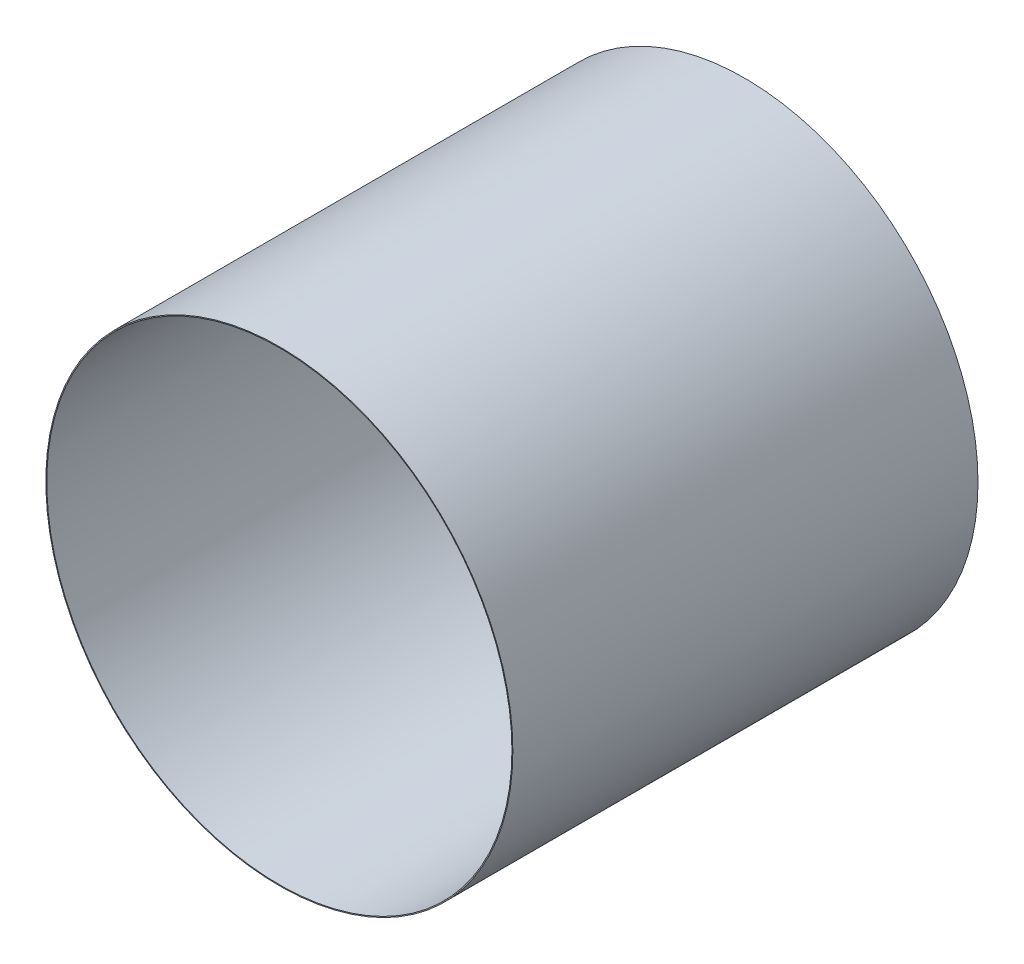
SolidWorks part; units mm, degrees
ref_plane "Front Plane" through (0, 0, 0) normal (0, 0, 1) x (1, 0, 0)
ref_plane "Top Plane" through (0, 0, 0) normal (0, 1, 0) x (1, 0, 0)
ref_plane "Right Plane" through (0, 0, 0) normal (1, 0, 0) x (0, 0, -1)
sketch "Sketch1" plane through (0, 0, 0) normal (0, 0, 1) x (1, 0, 0)
  circle A0 centre (0, 0) radius 12.55
  circle A1 centre (0, 0) radius 12.5
  dimension "D1" = 25
  dimension "D2" = 25.1
extrude "Boss-Extrude1" add sketch "Sketch1" along normal blind 25
